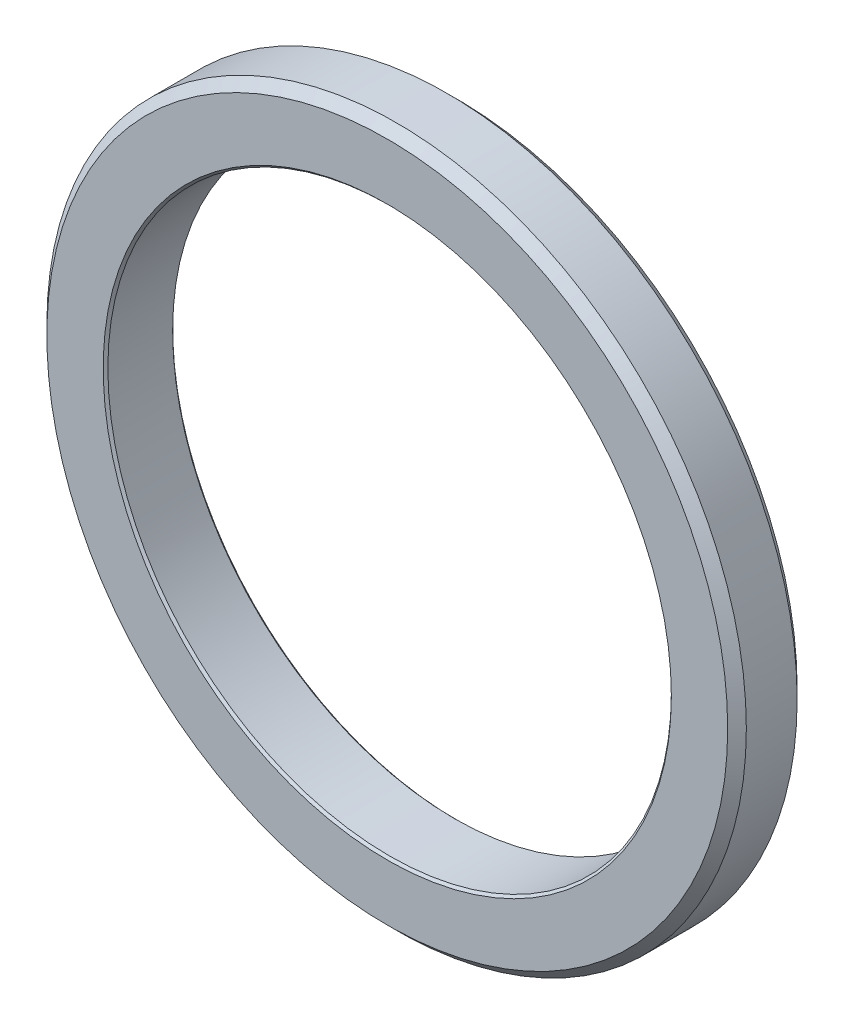
SolidWorks part; units mm, degrees
material "PETP Grey"
ref_plane "Front Plane" through (0, 0, 0) normal (0, 0, 1) x (1, 0, 0)
ref_plane "Top Plane" through (0, 0, 0) normal (0, 1, 0) x (1, 0, 0)
ref_plane "Right Plane" through (0, 0, 0) normal (1, 0, 0) x (0, 0, -1)
sketch "Sketch1" plane through (0, 0, 0) normal (1, 0, 0) x (0, 0, -1)
  line L0 (0, 0) -> (41.4438, 0) construction
  line L1 (0, 30.475) -> (0.25, 30.225)
  line L2 (1, 37.5195) -> (6.45, 37.5195)
  line L3 (0, 36.5195) -> (0, 30.475)
  line L4 (0.25, 30.225) -> (7.2, 30.225)
  line L5 (7.45, 36.5195) -> (7.45, 30.475)
  line L6 (7.2, 30.225) -> (7.45, 30.475)
  line L7 (0, 36.5195) -> (1, 37.5195)
  line L8 (6.45, 37.5195) -> (7.45, 36.5195)
  point P3 (0, 37.5195)
  point P4 (7.45, 30.225)
  point P5 (0, 30.225)
  point P6 (7.45, 37.5195)
  dimension "D1" = 60.45
  dimension "D2" = 75.039
  dimension "D3" = 7.45
revolve "Revolve1" add sketch "Sketch1" angle 360 about L0
